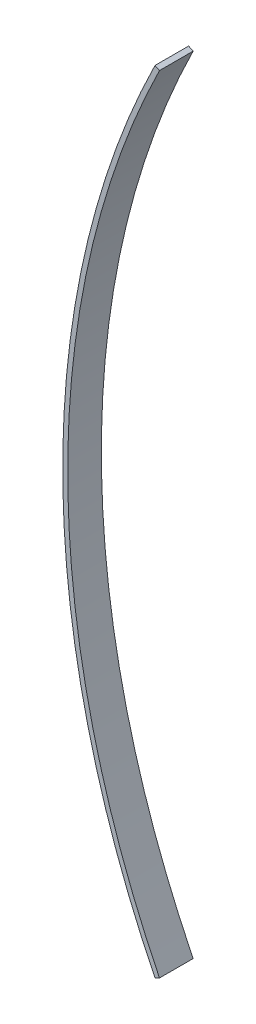
SolidWorks part; units mm, degrees
ref_plane "Front Plane" through (0, 0, 0) normal (0, 0, 1) x (1, 0, 0)
ref_plane "Top Plane" through (0, 0, 0) normal (0, 1, 0) x (1, 0, 0)
ref_plane "Right Plane" through (0, 0, 0) normal (1, 0, 0) x (0, 0, -1)
sketch "Sketch1" plane through (0, 0, 0) normal (0, 0, 1) x (1, 0, 0)
  arc B0 (164.1468, 89.4159) -> (164.1468, 79.1202) centre (165.1773, 84.268) ccw
  arc B1 (164.1468, 89.4159) -> (27.5816, 168.2619) centre (16.0718, -9.3656) ccw
  arc B2 (18.6652, 163.114) -> (27.5816, 168.2619) centre (22.6081, 166.5804) ccw
  arc B3 (18.6652, 163.114) -> (18.6652, 5.4221) centre (178.25, 84.268) ccw
  arc B4 (27.5816, 0.2742) -> (18.6652, 5.4221) centre (22.6081, 1.9557) ccw
  arc B5 (27.5816, 0.2742) -> (164.1468, 79.1202) centre (16.0718, 177.9017) ccw
  arc B6 (18.6136, 163.5731) -> (18.6136, 4.963) centre (178.25, 84.268) ccw
  arc B7 (27.2098, 0) -> (164.5701, 79.305) centre (16.0718, 177.9017) ccw
  arc B8 (164.5701, 89.231) -> (27.2098, 168.5361) centre (16.0718, -9.3656) ccw
  circle B9 centre (70.1312, 84.268) radius 63
  circle B10 centre (70.1312, 84.268) radius 59.5
  circle B11 centre (70.1312, 84.268) radius 58.5
  circle B12 centre (70.1312, 84.268) radius 55
sketch_block_instance "Seals Block-1"
sketch_block "Seals Block"
extrude "Extrude-Thin1" add sketch "Sketch1" against normal blind 6.75 thin contours B3
